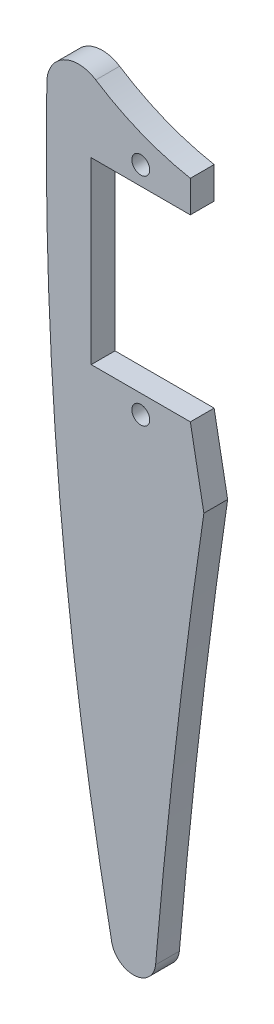
SolidWorks part; units mm, degrees
ref_plane "Alzado" through (0, 0, 0) normal (0, 0, 1) x (1, 0, 0)
ref_plane "Planta" through (0, 0, 0) normal (0, 1, 0) x (1, 0, 0)
ref_plane "Vista lateral" through (0, 0, 0) normal (1, 0, 0) x (0, 0, -1)
sketch "Croquis1" plane through (0, 0, 0) normal (0, 0, 1) x (1, 0, 0)
  line L0 (-29.143, -75.3) -> (34.6751, -75.3) construction
  line L1 (-6.25, 11.3) -> (6.25, 11.3)
  line L2 (-6.25, 11.3) -> (-6.25, -11.3)
  line L3 (-6.25, -11.3) -> (6.25, -11.3)
  line L5 (-6.25, 11.3) -> (6.25, -11.3) construction
  line L6 (-6.25, -11.3) -> (6.25, 11.3) construction
  line L7 (-6.25, -5.3) -> (6.25, -5.3) construction
  line L8 (0, -11.3) -> (0, -5.3) construction
  line L9 (0, -11.3) -> (0, -75.5) construction
  line L10 (6.25, 11.3) -> (13.25, 11.3) construction
  line L11 (-38.7974, 25.0272) -> (55.5686, 25.0272) construction
  line L12 (-6.25, -72.8) -> (10.9641, -72.8) construction
  line L13 (0, 11.3) -> (0, 15.3) construction
  line L14 (6.25, 11.3) -> (6.25, 15.3)
  line L16 (6.25, -11.3) -> (7.9548, -20.4259)
  circle A0 centre (0, -5.3) radius 1.3186
  arc A2 (-3.7138, -72.8) -> (1.8662, -72.8) centre (-0.9238, -72.4932) ccw
  arc A9 (7.9548, -20.4259) -> (1.8662, -72.8) centre (853.8453, -145.3035) ccw
  arc A12 (-10.765, 21.5374) -> (-3.7138, -72.8) centre (589.2294, 18.9516) ccw construction
  arc A13 (6.25, 15.3) -> (-5.6704, 20.082) centre (12.4257, 47.9432) cw
  arc A14 (-11.8486, 16.7954) -> (-3.7138, -72.8) centre (407.1802, 9.6742) ccw
  arc A15 (-5.6704, 20.082) -> (-11.8486, 16.7954) centre (-7.8492, 16.7274) ccw
  point P0 (0, 0)
  point P28 (-13.2157, 25.0272)
  point P32 (10.2683, 85.8587)
  point P33 (-11.6278, 25.0272)
  point P35 (-10.7277, 25.0272)
  point P37 (0, 0)
  point P39 (0, 0)
  dimension "D7" = 4
  dimension "D8" = 4
  dimension "D9" = 22.6
  dimension "D1" = 12.5
  dimension "D2" = 4
  dimension "D3" = 70
  dimension "D4" = 6
  dimension "D5" = 7
  dimension "D6" = 2.5
extrude "Saliente-Extruir1" add sketch "Croquis1" along normal blind 3
sketch "Croquis2" plane through (0, 0, 3) normal (0, 0, 1) x (1, 0, 0)
  line L0 (0, 11.3) -> (0, 13.65) construction
  line L1 (-6.25, 11.3) -> (6.25, 11.3) construction
  line L2 (0, -11.3) -> (0, -13.65) construction
  line L3 (-6.25, -11.3) -> (6.25, -11.3) construction
  circle A0 centre (0, 13.65) radius 1.125
  circle A1 centre (0, -13.65) radius 1.125
  dimension "D2" = 2.25
  dimension "D4" = 2.25
  dimension "D1" = 2.35
  dimension "D3" = 2.35
extrude "Cortar-Extruir1" cut sketch "Croquis2" against normal up to surface (3 mm away) up to face at (-0.9178, -11.5282, 0)
